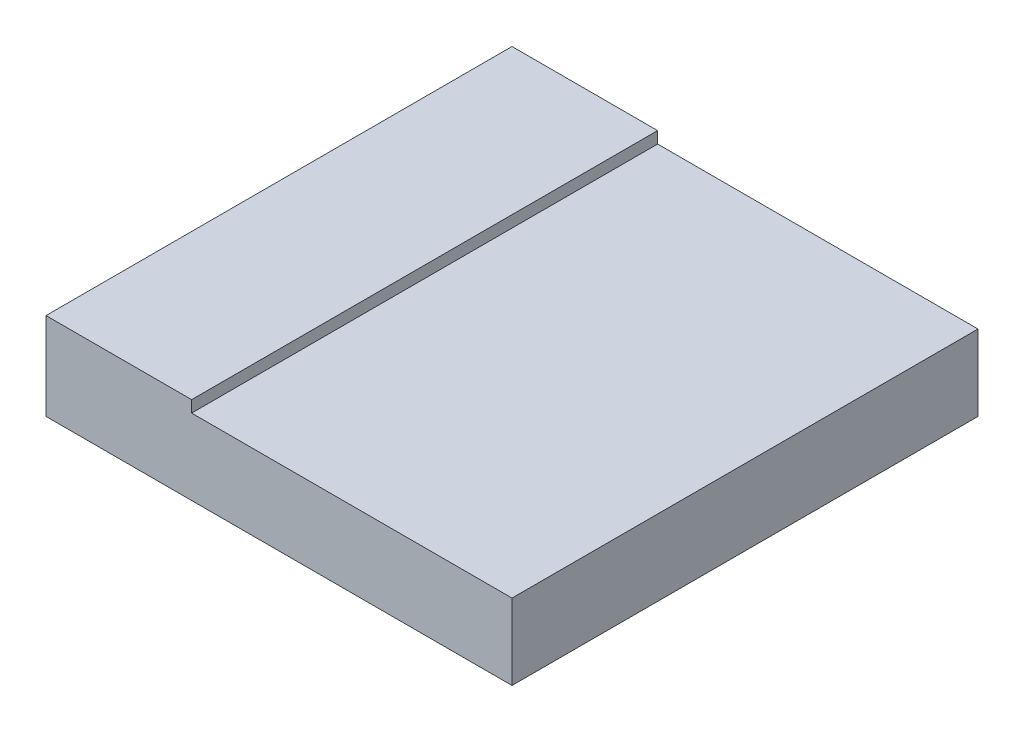
SolidWorks part; units mm, degrees
ref_plane "Front Plane" through (0, 0, 0) normal (0, 0, 1) x (1, 0, 0)
ref_plane "Top Plane" through (0, 0, 0) normal (0, 1, 0) x (1, 0, 0)
ref_plane "Right Plane" through (0, 0, 0) normal (1, 0, 0) x (0, 0, -1)
sketch "Sketch1" plane through (0, 0, 0) normal (0, 1, 0) x (1, 0, 0)
  line L1 (0, 0) -> (101.6, 0)
  line L2 (0, 0) -> (0, 101.6)
  line L3 (0, 101.6) -> (101.6, 101.6)
  line L4 (101.6, 0) -> (101.6, 101.6)
  dimension "D1" = 101.6
extrude "Boss-Extrude1" add sketch "Sketch1" along normal blind 19.05
sketch "Sketch2" plane through (0, 19.05, 0) normal (0, 1, 0) x (1, 0, 0)
  line L0 (101.6, 101.6) -> (0, 101.6) construction
  line L1 (101.6, 0) -> (31.75, 0)
  line L2 (101.6, 0) -> (101.6, 101.6)
  line L3 (101.6, 101.6) -> (31.75, 101.6)
  line L4 (31.75, 0) -> (31.75, 101.6)
  dimension "D1" = 69.85
extrude "Cut-Extrude1" cut sketch "Sketch2" against normal blind 2.54
